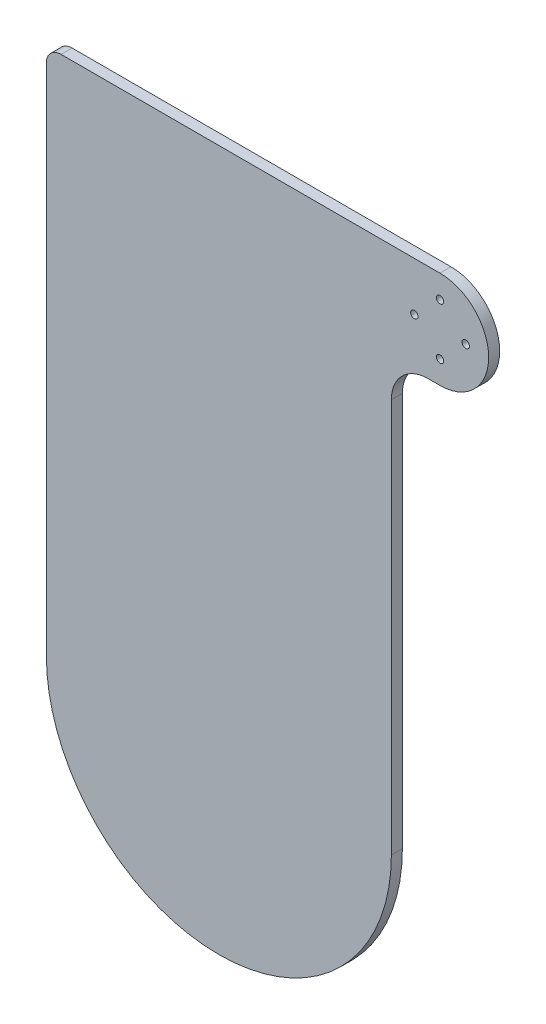
SolidWorks part; units mm, degrees
material "ABS"
ref_plane "前视基准面" through (0, 0, 0) normal (0, 0, 1) x (1, 0, 0)
ref_plane "上视基准面" through (0, 0, 0) normal (0, 1, 0) x (1, 0, 0)
ref_plane "右视基准面" through (0, 0, 0) normal (1, 0, 0) x (0, 0, -1)
sketch "草图1" plane through (0, 0, 0) normal (0, 0, 1) x (1, 0, 0)
  line L0 (-60.5688, -43.6094) -> (-60.5688, 100.2906)
  line L1 (33.4312, -43.6094) -> (33.4312, 63.7906)
  line L2 (46.6812, 100.2906) -> (33.4312, 100.2906)
  line L3 (33.4312, 100.2906) -> (-60.5688, 100.2906)
  line L4 (46.6812, 73.7906) -> (43.4312, 73.7906)
  arc A0 (-60.5688, -43.6094) -> (33.4312, -43.6094) centre (-13.5688, -43.6094) ccw
  arc A1 (46.6812, 73.7906) -> (46.6812, 100.2906) centre (46.6812, 87.0406) ccw
  arc A2 (33.4312, 63.7906) -> (43.4312, 73.7906) centre (43.4312, 63.7906) cw
  dimension "D1" = 10
extrude "凸台-拉伸1" add sketch "草图1" along normal blind 3
sketch "草图2" plane through (0, 0, 0) normal (0, 0, -1) x (-1, 0, 0)
  circle A0 centre (-46.6812, 87.0406) radius 7 construction
  circle A1 centre (-46.6812, 94.0406) radius 1
  circle A2 centre (-39.6812, 87.0406) radius 1
  circle A3 centre (-46.6812, 80.0406) radius 1
  circle A4 centre (-53.6812, 87.0406) radius 1
  point P14 (-51.6812, 82.0406)
  point P18 (-46.6812, 87.0406)
  dimension "D1" = 14
  dimension "D2" = 2
  dimension "D3" = 4
extrude "切除-拉伸1" cut sketch "草图2" against normal blind 10
fillet "圆角1" radius 4 1 edges at (-60.5688, 100.2906, 1.5)
